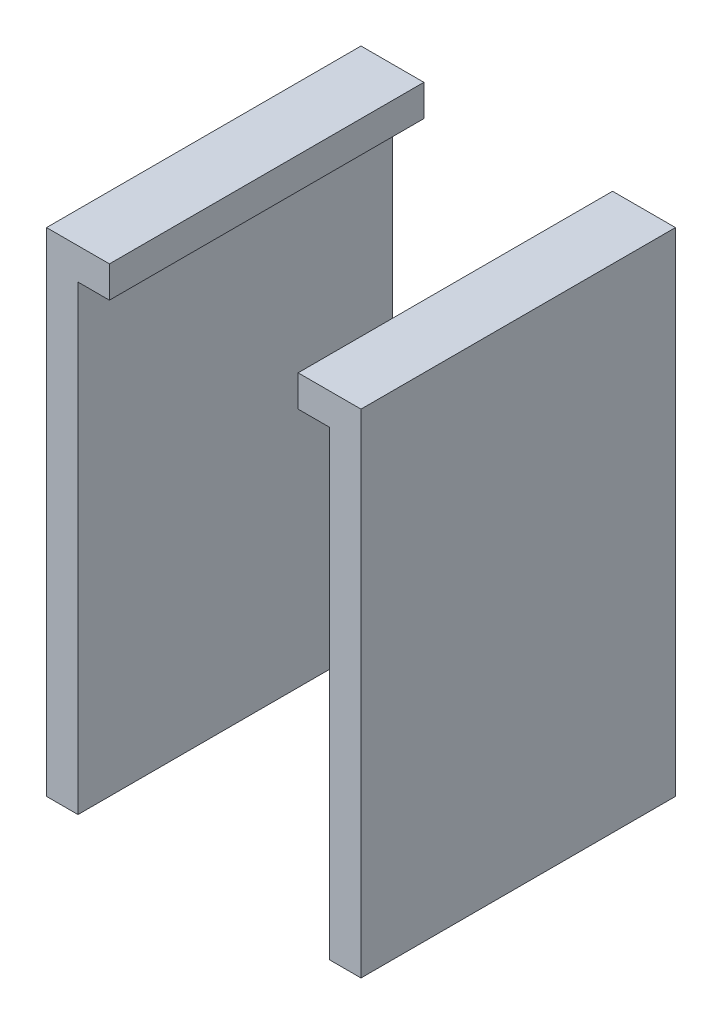
SolidWorks part; units mm, degrees
ref_plane "Front Plane" through (0, 0, 0) normal (0, 0, 1) x (1, 0, 0)
ref_plane "Top Plane" through (0, 0, 0) normal (0, 1, 0) x (1, 0, 0)
ref_plane "Right Plane" through (0, 0, 0) normal (1, 0, 0) x (0, 0, -1)
sketch "Sketch1" plane through (0, 0, 0) normal (0, 0, 1) x (1, 0, 0)
  line L0 (0, 0) -> (0, 235)
  line L1 (0, 235) -> (30, 235)
  line L2 (30, 235) -> (30, 220)
  line L3 (30, 220) -> (15, 220)
  line L4 (15, 220) -> (15, 0)
  line L5 (15, 0) -> (0, 0)
  line L6 (135, 0) -> (135, 220)
  line L7 (135, 220) -> (120, 220)
  line L8 (120, 220) -> (120, 235)
  line L9 (120, 235) -> (150, 235)
  line L10 (150, 235) -> (150, 0)
  line L11 (150, 0) -> (135, 0)
  point P9 (30, 227.5)
  dimension "D1" = 235
  dimension "D2" = 15
  dimension "D3" = 15
  dimension "D4" = 30
  dimension "D6" = 90
extrude "Boss-Extrude1" add sketch "Sketch1" along normal blind 150
